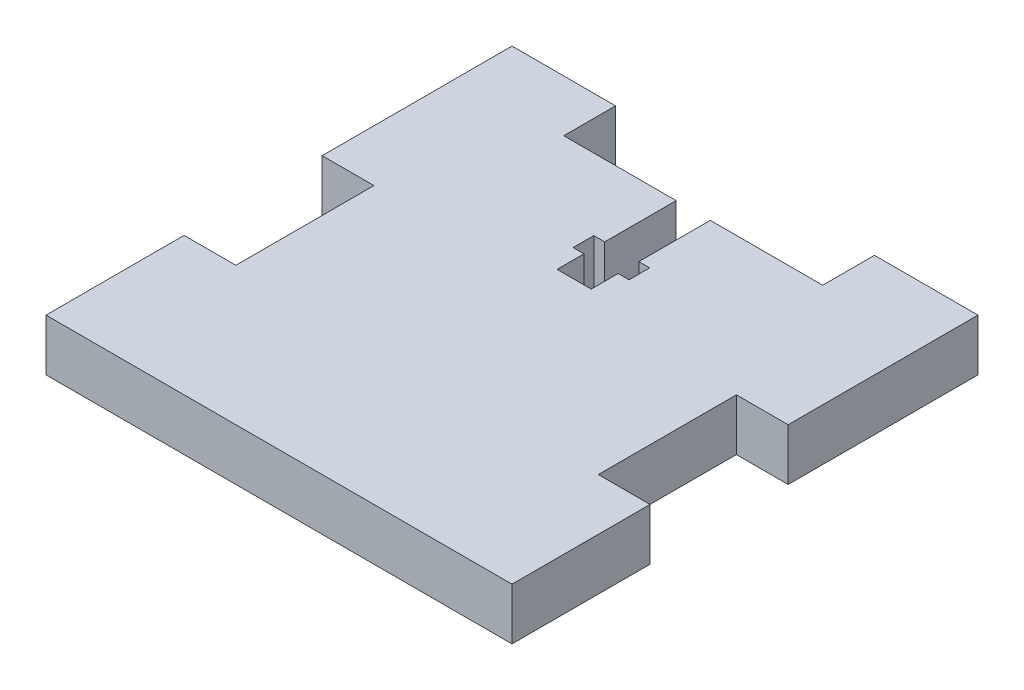
SolidWorks part; units mm, degrees
ref_plane "Front Plane" through (0, 0, 0) normal (0, 0, 1) x (1, 0, 0)
ref_plane "Top Plane" through (0, 0, 0) normal (0, 1, 0) x (1, 0, 0)
ref_plane "Right Plane" through (0, 0, 0) normal (1, 0, 0) x (0, 0, -1)
sketch "Sketch1" plane through (0, 0, 0) normal (0, 0, 1) x (1, 0, 0)
  line L1 (-22.225, 14.2875) -> (22.225, 14.2875) construction
  line L2 (-22.225, 14.2875) -> (-22.225, -14.2875) construction
  line L3 (-22.225, -14.2875) -> (22.225, -14.2875) construction
  line L4 (22.225, 14.2875) -> (22.225, -14.2875) construction
  line L5 (-22.225, 14.2875) -> (22.225, -14.2875) construction
  line L6 (-22.225, -14.2875) -> (22.225, 14.2875) construction
  line L7 (-22.225, -14.2875) -> (22.225, -14.2875)
  line L8 (-22.225, -14.2875) -> (-22.225, -20.6375)
  line L9 (-22.225, -20.6375) -> (22.225, -20.6375)
  line L10 (22.225, -14.2875) -> (22.225, -20.6375)
  point P0 (0, 0)
  dimension "D1" = 44.45
  dimension "D2" = 28.575
  dimension "D3" = 6.35
extrude "Boss-Extrude1" add sketch "Sketch1" along normal blind 50.8
ref_plane "Plane1" through (0, 0, 0) normal (1, 0, 0) x (0, 0, -1)
sketch "Sketch2" plane through (-22.225, 0, 0) normal (-1, 0, 0) x (0, 0, 1)
  line L0 (50.8, -14.2875) -> (0, -14.2875) construction
  line L1 (50.8, -20.6375) -> (33.8667, -20.6375)
  line L2 (50.8, -20.6375) -> (50.8, -14.2875)
  line L3 (50.8, -14.2875) -> (33.8667, -14.2875)
  line L4 (33.8667, -20.6375) -> (33.8667, -14.2875)
  line L5 (16.9333, -20.6375) -> (33.8667, -20.6375) construction
  line L6 (0, -20.6375) -> (16.9333, -20.6375)
  line L7 (0, -20.6375) -> (0, -14.2875)
  line L8 (0, -14.2875) -> (16.9333, -14.2875)
  line L9 (16.9333, -20.6375) -> (16.9333, -14.2875)
extrude "Boss-Extrude2" add sketch "Sketch2" along normal up to surface (6.35 mm away) and the other way offset from surface (50.8 mm away) 6.35 other way up to face at (22.225, -17.4625, 25.4)
sketch "Sketch4" plane through (0, 0, 0) normal (0, 0, -1) x (-1, 0, 0)
  line L0 (28.575, -20.6375) -> (-28.575, -20.6375) construction
  line L1 (28.575, -20.6375) -> (15.875, -20.6375)
  line L2 (28.575, -20.6375) -> (28.575, -14.2875)
  line L3 (28.575, -14.2875) -> (15.875, -14.2875)
  line L4 (15.875, -20.6375) -> (15.875, -14.2875)
  line L5 (-28.575, -14.2875) -> (28.575, -14.2875) construction
  line L6 (28.575, -20.6375) -> (28.575, -14.2875) construction
  line L8 (-28.575, -20.6375) -> (-15.875, -20.6375)
  line L9 (-28.575, -20.6375) -> (-28.575, -14.2875)
  line L10 (-28.575, -14.2875) -> (-15.875, -14.2875)
  line L11 (-15.875, -20.6375) -> (-15.875, -14.2875)
  dimension "D1" = 12.7
extrude "Boss-Extrude4" add sketch "Sketch4" along normal blind 6.35
sketch "Sketch5" plane through (0, -20.6375, 0) normal (0, -1, 0) x (-1, 0, 0)
  line L0 (15.875, 0) -> (-15.875, 0) construction
  line L1 (0, 0) -> (0, -29.5961) construction
  line L2 (15.875, 6.35) -> (15.875, 0) construction
  line L3 (-15.875, 6.35) -> (-15.875, 0) construction
  line B0 (2.0955, 0) -> (-2.0955, 0)
  line B1 (-2.0955, -11.303) -> (-3.429, -11.303)
  line B2 (-3.429, -11.303) -> (-3.429, -8.763)
  line B3 (-3.429, -8.763) -> (-2.0955, -8.763)
  line B4 (-2.0955, -8.763) -> (-2.0955, 0)
  line B5 (-2.0955, -11.303) -> (-2.0955, -14.605)
  line B6 (-2.0955, -14.605) -> (2.0955, -14.605)
  line B7 (2.0955, -11.303) -> (2.0955, -14.605)
  line B8 (2.0955, -8.763) -> (2.0955, 0)
  line B9 (3.429, -8.763) -> (2.0955, -8.763)
  line B10 (3.429, -11.303) -> (3.429, -8.763)
  line B11 (2.0955, -11.303) -> (3.429, -11.303)
sketch_block_instance "TSlot-1"
sketch_block "TSlot" parameters "D1"=3.302, "D2"=2.54, "D3"=3.175, "D4"=8.763, "D5"=1.3462
extrude "Cut-Extrude1" cut sketch "Sketch5" against normal through all
